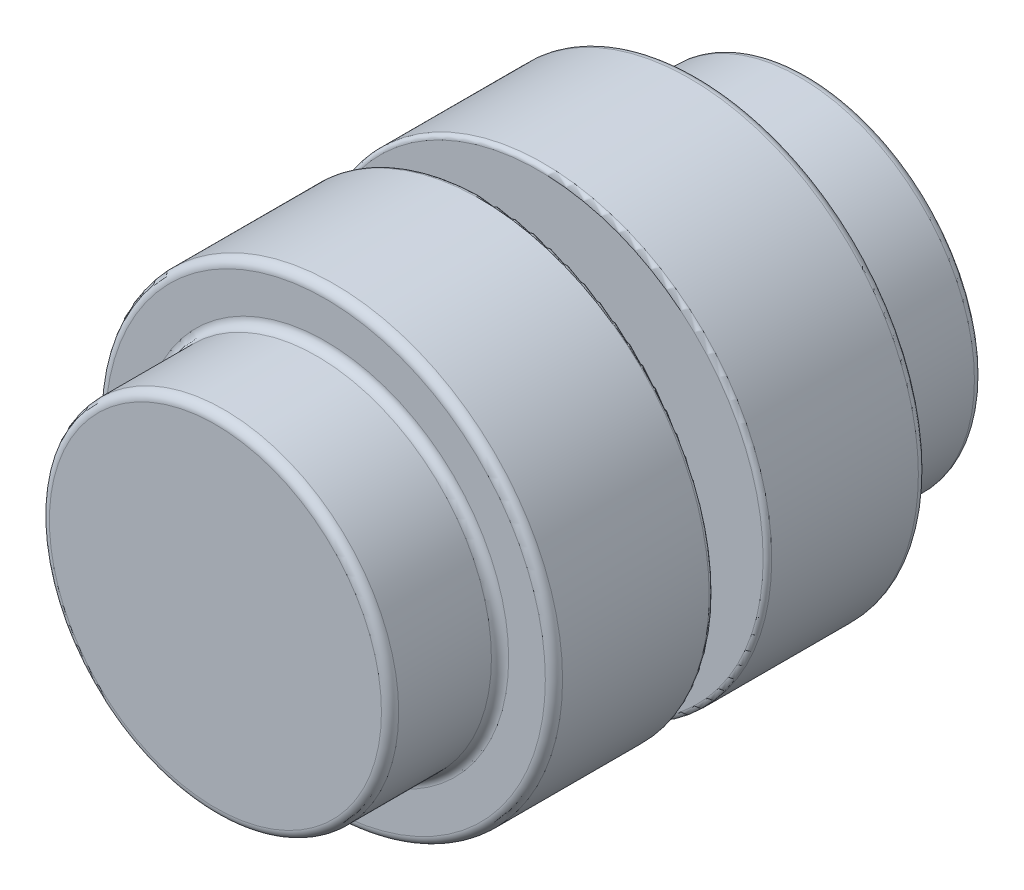
SolidWorks part; units mm, degrees
ref_plane "Front Plane" through (0, 0, 0) normal (0, 0, 1) x (1, 0, 0)
ref_plane "Top Plane" through (0, 0, 0) normal (0, 1, 0) x (1, 0, 0)
ref_plane "Right Plane" through (0, 0, 0) normal (1, 0, 0) x (0, 0, -1)
sketch "Sketch1" plane through (0, 0, 0) normal (1, 0, 0) x (0, 0, -1)
  line L0 (-121.4977, 0) -> (114.1883, 0) construction
  line L1 (-17.4625, 0) -> (-17.4625, 9.779)
  line L2 (-16.9545, 10.287) -> (-11.4935, 10.287)
  line L3 (-10.9855, 10.795) -> (-10.9855, 12.954)
  line L4 (-10.4775, 13.462) -> (-1.8415, 13.462)
  line L5 (-1.5875, 13.208) -> (-1.5875, 0)
  line L6 (-1.5875, 0) -> (-17.4625, 0)
  line L7 (0, 55) -> (0, -55) construction
  arc A0 (-17.4625, 9.779) -> (-16.9545, 10.287) centre (-16.9545, 9.779) cw
  arc A1 (-11.4935, 10.287) -> (-10.9855, 10.795) centre (-11.4935, 10.795) ccw
  arc A2 (-10.9855, 12.954) -> (-10.4775, 13.462) centre (-10.4775, 12.954) cw
  arc A3 (-1.8415, 13.462) -> (-1.5875, 13.208) centre (-1.8415, 13.208) cw
  dimension "D6" = 0.508
  dimension "D7" = 0.254
  dimension "D1" = 20.574
  dimension "D2" = 1.5875
  dimension "D3" = 26.924
  dimension "D4" = 15.875
  dimension "D5" = 9.398
revolve "Revolve1" add sketch "Sketch1" angle 360 about L0
mirror "Mirror1" about plane through (0, 0, 0) normal (0, 0, 1) of bodies 102
